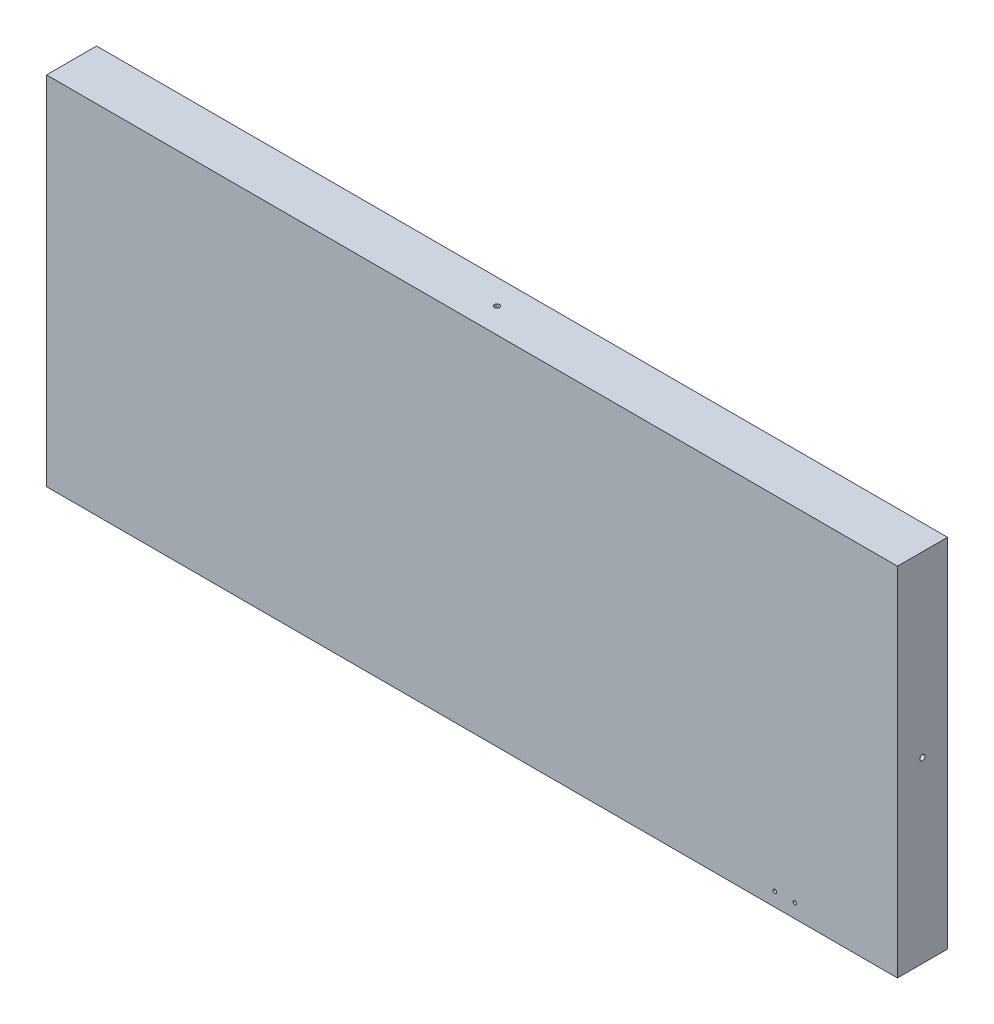
SolidWorks part; units mm, degrees
material "1.4511 (X3CrNb17)"
ref_plane "前视基准面" through (0, 0, 0) normal (0, 0, 1) x (1, 0, 0)
ref_plane "上视基准面" through (0, 0, 0) normal (0, 1, 0) x (1, 0, 0)
ref_plane "右视基准面" through (0, 0, 0) normal (1, 0, 0) x (0, 0, -1)
sketch "草图1" plane through (0, 0, 0) normal (0, 0, 1) x (1, 0, 0)
  line L1 (-340, 142.5) -> (340, 142.5)
  line L2 (-340, 142.5) -> (-340, -142.5)
  line L3 (-340, -142.5) -> (340, -142.5)
  line L4 (340, 142.5) -> (340, -142.5)
  line L5 (-340, 142.5) -> (340, -142.5) construction
  line L6 (-340, -142.5) -> (340, 142.5) construction
  point P0 (0, 0)
  dimension "D1" = 680
  dimension "D2" = 285
extrude "凸台-拉伸1" add sketch "草图1" along normal blind 40
sketch "草图2" plane through (0, -142.5, 0) normal (0, -1, 0) x (1, 0, 0)
  line L0 (-340, 40) -> (-340, 0) construction
  point P0 (0, 20)
  dimension "D1" = 340
hole_wizard "M5 螺纹孔1" positions "草图3" profile "草图4" tap size "M5" standard "GB" end condition through all
sketch "草图3" plane through (0, -142.5, 0) normal (0, -1, 0) x (-1, 0, 0)
  point P0 (0, -20)
sketch "草图4" plane through (0, -142.5, 20) normal (1, 0, 0) x (0, 0, -1)
  line L0 (0, 0) -> (0, 285)
  line L1 (0, 285) -> (2.1, 285)
  line L2 (2.1, 285) -> (2.1, 0)
  line L5 (2.1, 0) -> (0, 0)
  line L11 (0, -6.35) -> (0, 107.95) construction
  dimension "通孔螺纹孔钻头直径" = 4.2
  dimension "通孔螺纹孔钻头深度" = 285
cosmetic thread "孔螺蚊线1" parameters "D2"=5
sketch "草图5" plane through (-340, 0, 0) normal (-1, 0, 0) x (0, 0, 1)
  line L0 (40, 142.5) -> (0, 142.5) construction
  point P0 (20, 0)
  dimension "D1" = 142.5
hole_wizard "M5 螺纹孔2" positions "草图6" profile "草图7" tap size "M5" standard "GB" end condition through all
sketch "草图6" plane through (-340, 0, 0) normal (-1, 0, 0) x (0, 0, 1)
  point P0 (20, 0)
sketch "草图7" plane through (-340, 0, 20) normal (0, 1, 0) x (0, 0, 1)
  line L0 (0, 0) -> (0, 680)
  line L1 (0, 680) -> (2.1, 680)
  line L2 (2.1, 680) -> (2.1, 0)
  line L5 (2.1, 0) -> (0, 0)
  line L11 (0, -6.35) -> (0, 107.95) construction
  dimension "通孔螺纹孔钻头直径" = 4.2
  dimension "通孔螺纹孔钻头深度" = 680
cosmetic thread "孔螺蚊线2" parameters "D2"=5
sketch "草图8" plane through (0, 0, 40) normal (0, 0, 1) x (1, 0, 0)
  line L0 (242, -131.5) -> (258, -131.5) construction
  line L1 (-340, -142.5) -> (340, -142.5) construction
  line L2 (340, -142.5) -> (340, 142.5) construction
  point P2 (0, 0)
  dimension "D1" = 16
  dimension "D2" = 11
  dimension "D3" = 82
hole_wizard "M3.5 螺纹孔1" positions "草图9" profile "草图10" tap size "M3.5" standard "GB"
sketch "草图9" plane through (0, 0, 40) normal (0, 0, 1) x (1, 0, 0)
  point P0 (258, -131.5)
  point P3 (242, -131.5)
sketch "草图10" plane through (258, -131.5, 40) normal (1, 0, 0) x (0, -1, 0)
  line L0 (0, 0) -> (0, 8.2712)
  line L1 (0, 8.2712) -> (1.45, 7.4)
  line L2 (1.45, 7.4) -> (1.45, 0)
  line L5 (1.45, 0) -> (0, 0)
  line L10 (0, 8.2712) -> (-1.45, 7.4) construction
  line L11 (0, -6.35) -> (0, 107.95) construction
  dimension "螺纹孔钻头直径" = 2.9
  dimension "螺纹孔钻头深度" = 7.4
  dimension "导头角度" = 118
cosmetic thread "孔螺蚊线3" parameters "D1"=4.4, "D2"=3.5
cosmetic thread "孔螺蚊线4" parameters "D1"=4.4, "D2"=3.5
